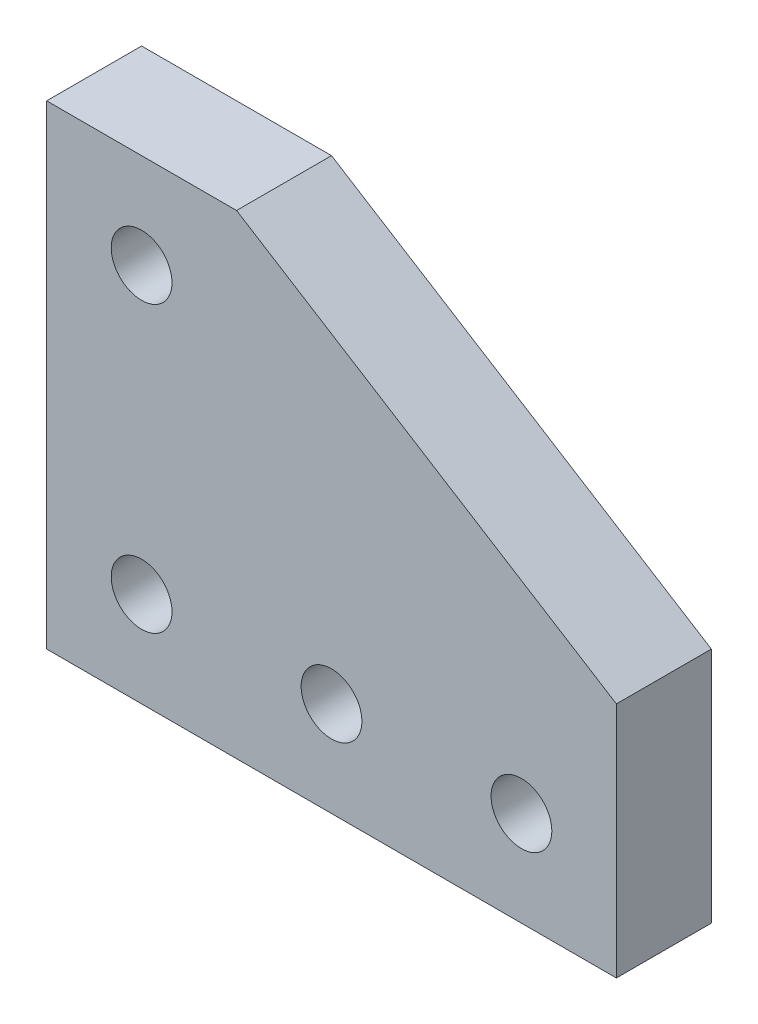
SolidWorks part; units mm, degrees
ref_plane "正面" through (0, 0, 0) normal (0, 0, 1) x (1, 0, 0)
ref_plane "平面" through (0, 0, 0) normal (0, 1, 0) x (1, 0, 0)
ref_plane "右側面" through (0, 0, 0) normal (1, 0, 0) x (0, 0, -1)
sketch "Sketch1" plane through (0, 0, 0) normal (0, 0, 1) x (1, 0, 0)
  line L1 (-15, 12.5) -> (15, 12.5)
  line L2 (-15, 12.5) -> (-15, -12.5)
  line L3 (-15, -12.5) -> (15, -12.5)
  line L4 (15, 12.5) -> (15, -12.5)
  line L5 (-15, 12.5) -> (15, -12.5) construction
  line L6 (-15, -12.5) -> (15, 12.5) construction
  point P0 (0, 0)
  dimension "D1" = 25
  dimension "D2" = 30
extrude "Boss-Extrude1" add sketch "Sketch1" along normal blind 5
sketch "Sketch2" plane through (0, 0, 5) normal (0, 0, 1) x (1, 0, 0)
  line L0 (-15, -7.5) -> (15, -7.5) construction
  line L1 (-15, 12.5) -> (-15, -12.5) construction
  line L2 (15, -12.5) -> (15, 12.5) construction
  line L3 (-15, 7.5) -> (15, 7.5) construction
  line L4 (15, 12.5) -> (-15, 12.5) construction
  line L5 (-15, -12.5) -> (15, -12.5) construction
  line L6 (-10, -7.5) -> (0, -7.5) construction
  line L7 (-10, -7.5) -> (-10, 7.5) construction
  circle A0 centre (-10, -7.5) radius 1.6
  circle A1 centre (0, -7.5) radius 1.6
  circle A2 centre (10, -7.5) radius 1.6
  circle A4 centre (-10, 7.5) radius 1.6
  dimension "D3" = 3.2
  dimension "D1" = 5
  dimension "D2" = 5
  dimension "D4" = 5
  dimension "D6" = 10
  dimension "D8" = 15
  dimension "D5" = 3
  dimension "D7" = 2
extrude "Cut-Extrude1" cut sketch "Sketch2" against normal up to next
sketch "Sketch3" plane through (0, 0, 5) normal (0, 0, 1) x (1, 0, 0)
  line L0 (-5, 12.5) -> (15, 0)
  line L1 (15, 12.5) -> (-15, 12.5) construction
  line L2 (15, -12.5) -> (15, 12.5) construction
  line L3 (-15, 12.5) -> (-15, -12.5) construction
  dimension "D1" = 10
extrude "Cut-Extrude2" cut sketch "Sketch3" against normal blind 5 and the other way through all
